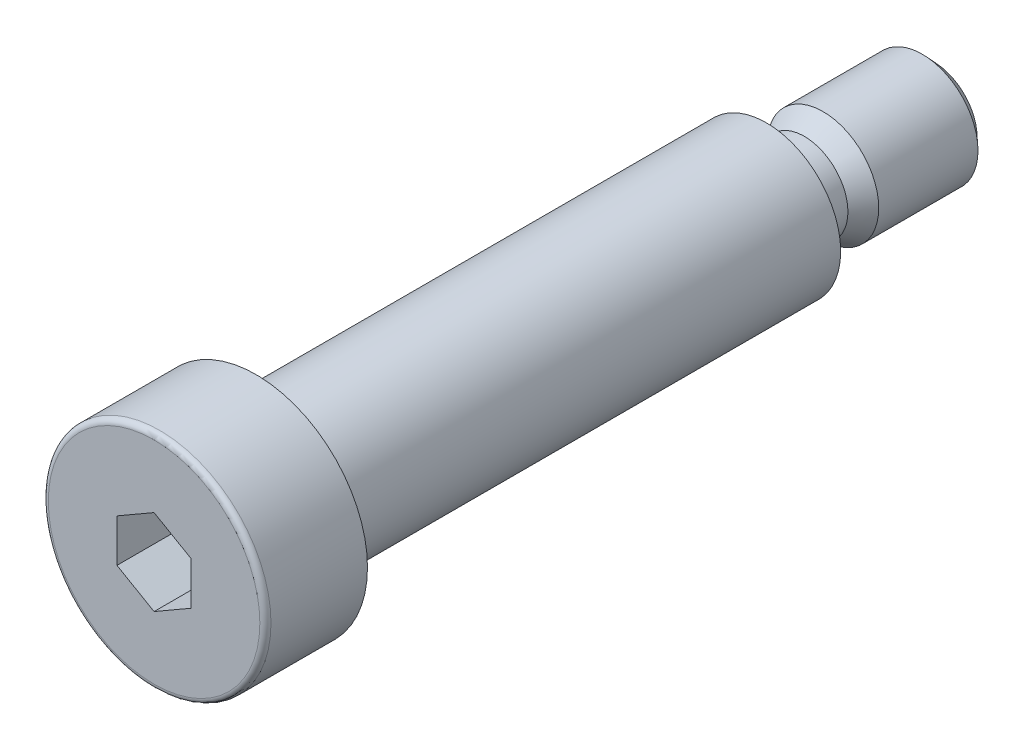
SolidWorks part; units mm, degrees
material "1.0545 (S355N)"
ref_plane "Płaszczyzna przednia" through (0, 0, 0) normal (0, 0, 1) x (1, 0, 0)
ref_plane "Płaszczyzna górna" through (0, 0, 0) normal (0, 1, 0) x (1, 0, 0)
ref_plane "Płaszczyzna prawa" through (0, 0, 0) normal (1, 0, 0) x (0, 0, -1)
sketch "Szkic1" plane through (0, 0, 0) normal (0, 1, 0) x (1, 0, 0)
  line L0 (6, 33.6) -> (4.7, 31.58)
  line L1 (12, -38.5) -> (-12, -38.5)
  line L2 (12, -38.5) -> (12, -27.5)
  line L3 (12, -27.5) -> (-12, -27.5)
  line L4 (-12, -38.5) -> (-12, -27.5)
  line L5 (8, -27.5) -> (-8, -27.5)
  line L6 (8, -27.5) -> (8, 27.5)
  line L7 (8, 27.5) -> (-8, 27.5)
  line L8 (-8, -27.5) -> (-8, 27.5)
  line L9 (-4.7, 27.5) -> (4.7, 27.5)
  line L10 (-4.7, 27.5) -> (-4.7, 31.58)
  line L11 (-4.7, 31.58) -> (4.7, 31.58)
  line L12 (4.7, 27.5) -> (4.7, 31.58)
  line L13 (6, 33.6) -> (6, 44.3)
  line L14 (6, 44.3) -> (4.7, 45.5)
  line L15 (4.7, 45.5) -> (-4.7, 45.5)
  line L16 (-4.7, 45.5) -> (-6, 44.3)
  line L17 (-6, 44.3) -> (-6, 33.6)
  line L18 (-6, 33.6) -> (-4.7, 31.58)
  line L19 (6, 33.6) -> (-6, 33.6) construction
  line L20 (6, 44.3) -> (-6, 44.3) construction
  line L21 (0, -19.9356) -> (0, 25.6583) construction
  line L22 (0, -38.5) -> (0, 45.5)
  point P4 (0, -27.5)
  point P14 (0, -27.5)
  point P15 (0, 27.5)
  point P16 (0, 27.5)
  point P17 (-8, 0)
  point P23 (0, 33.6)
  point P25 (0, 45.5)
  point P26 (0, 31.58)
  point P27 (0, 44.3)
  dimension "D1" = 24
  dimension "D2" = 11
  dimension "D3" = 16
  dimension "l1" = 55
  dimension "D5" = 9.4
  dimension "D6" = 18
  dimension "D7" = 12
  dimension "D8" = 9.4
  dimension "D9" = 1.2
  dimension "D10" = 2.02
  dimension "D11" = 10.7
revolve "Obrót1" add sketch "Szkic1" angle 360 about L22
sketch "Szkic2" plane through (0, 0, 38.5) normal (0, 0, 1) x (1, 0, 0)
  line L1 (4, 2.3094) -> (0, 4.6188)
  line L2 (0, 4.6188) -> (-4, 2.3094)
  line L3 (-4, 2.3094) -> (-4, -2.3094)
  line L4 (-4, -2.3094) -> (0, -4.6188)
  line L5 (0, -4.6188) -> (4, -2.3094)
  line L6 (4, -2.3094) -> (4, 2.3094)
  circle A0 centre (0, 0) radius 4 construction
  dimension "D1" = 8
extrude "Wytnij-wyciągnięcie1" cut sketch "Szkic2" against normal blind 6.6
fillet "Zaokrąglenie1" radius 0.6 1 edges at (12, 0, 38.5)
